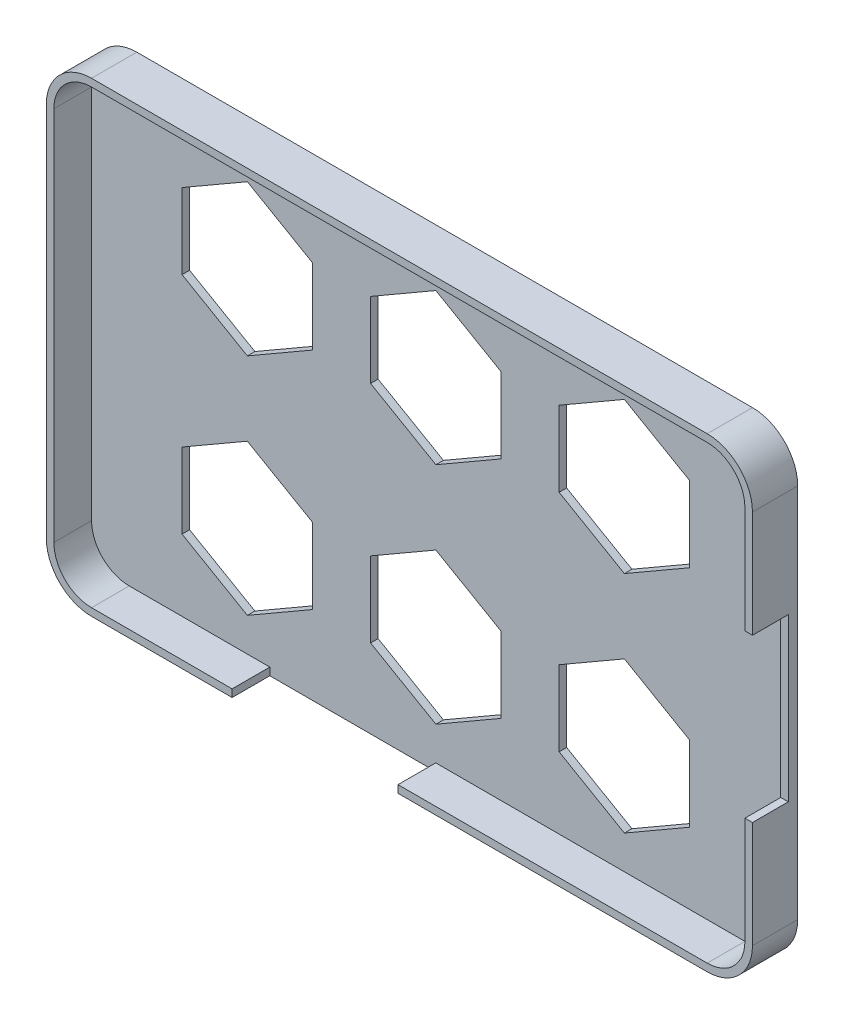
SolidWorks part; units mm, degrees
ref_plane "Ebene vorne" through (0, 0, 0) normal (1, 0, 0) x (0, 1, 0)
ref_plane "Ebene oben" through (0, 0, 0) normal (0, 0, 1) x (0, 1, 0)
ref_plane "Ebene rechts" through (0, 0, 0) normal (0, 1, 0) x (-1, 0, 0)
sketch "Skizze1" plane through (0, 0, 0) normal (0, 0, 1) x (0, 1, 0)
  line L0 (-30.9, -46.82) -> (30.9, -46.82)
  line L1 (-30.9, -46.82) -> (-30.9, 46.82)
  line L2 (-30.9, 46.82) -> (30.9, 46.82)
  line L3 (30.9, -46.82) -> (30.9, 46.82)
  line L4 (-30.9, -46.82) -> (30.9, 46.82) construction
  line L5 (-30.9, 46.82) -> (30.9, -46.82) construction
  point P0 (0, 0)
  point P5 (0, 0)
  dimension "D1" = 61.8
  dimension "D2" = 93.64
extrude "Aufsatz-Linear austragen1" add sketch "Skizze1" along normal blind 6
fillet "Verrundung1" radius 6 4 edges at (46.82, -30.9, 3) (-46.82, -30.9, 3) (-46.82, 30.9, 3) (46.82, 30.9, 3)
shell "Wandung1" thickness 1
sketch "Skizze2" plane through (46.82, 0, 0) normal (1, 0, 0) x (0, 1, 0)
  line L0 (-24.9, 6) -> (24.9, 6) construction
  line L1 (-10.75, 10.75) -> (10.75, 10.75)
  line L2 (-10.75, 10.75) -> (-10.75, 1.25)
  line L3 (-10.75, 1.25) -> (10.75, 1.25)
  line L4 (10.75, 10.75) -> (10.75, 1.25)
  line L5 (-10.75, 10.75) -> (10.75, 1.25) construction
  line L6 (-10.75, 1.25) -> (10.75, 10.75) construction
  point P0 (0, 6)
  dimension "D1" = 21.5
  dimension "D2" = 9.5
extrude "Schnitt-Linear austragen1" cut sketch "Skizze2" against normal blind 6
sketch "Skizze3" plane through (0, -30.9, 0) normal (0, -1, 0) x (1, 0, 0)
  line L0 (-40.82, 6) -> (40.82, 6) construction
  line L1 (-0.18, 6) -> (-22.18, 6)
  line L2 (-0.18, 6) -> (-0.18, 1)
  line L3 (-0.18, 1) -> (-22.18, 1)
  line L4 (-22.18, 6) -> (-22.18, 1)
  dimension "D1" = 22
  dimension "D2" = 5
  dimension "D3" = 41
extrude "Schnitt-Linear austragen2" cut sketch "Skizze3" against normal blind 6
sketch "Skizze4" plane through (0, 0, 0) normal (0, 0, -1) x (1, 0, 0)
  line L0 (-33.82, 30.9) -> (-33.82, -30.9) construction
  line L2 (-25.1597, 25.45) -> (-33.82, 20.45)
  line L3 (-33.82, 20.45) -> (-33.82, 10.45)
  line L4 (-33.82, 10.45) -> (-25.1597, 5.45)
  line L5 (-25.1597, 5.45) -> (-16.4995, 10.45)
  line L6 (-16.4995, 10.45) -> (-16.4995, 20.45)
  line L7 (-16.4995, 20.45) -> (-25.1597, 25.45)
  line L8 (-25.1597, -4.35) -> (-33.82, -9.35)
  line L9 (-33.82, -9.35) -> (-33.82, -19.35)
  line L10 (-33.82, -19.35) -> (-25.1597, -24.35)
  line L11 (-25.1597, -24.35) -> (-16.4995, -19.35)
  line L12 (-16.4995, -19.35) -> (-16.4995, -9.35)
  line L13 (-16.4995, -9.35) -> (-25.1597, -4.35)
  line L14 (-46.82, -24.9) -> (-46.82, 24.9) construction
  circle A8 centre (-25.1597, 15.45) radius 8.6603 construction
  dimension "D3" = 10.45
  dimension "D4" = 2
  dimension "D5" = 13
  dimension "D1" = 10
  dimension "D2" = 61.8
extrude "Schnitt-Linear austragen4" cut sketch "Skizze4" against normal blind 6
pattern_linear "Lineares Muster1" count 3 spacing 25 along (1, 0, 0) of "Schnitt-Linear austragen4"
